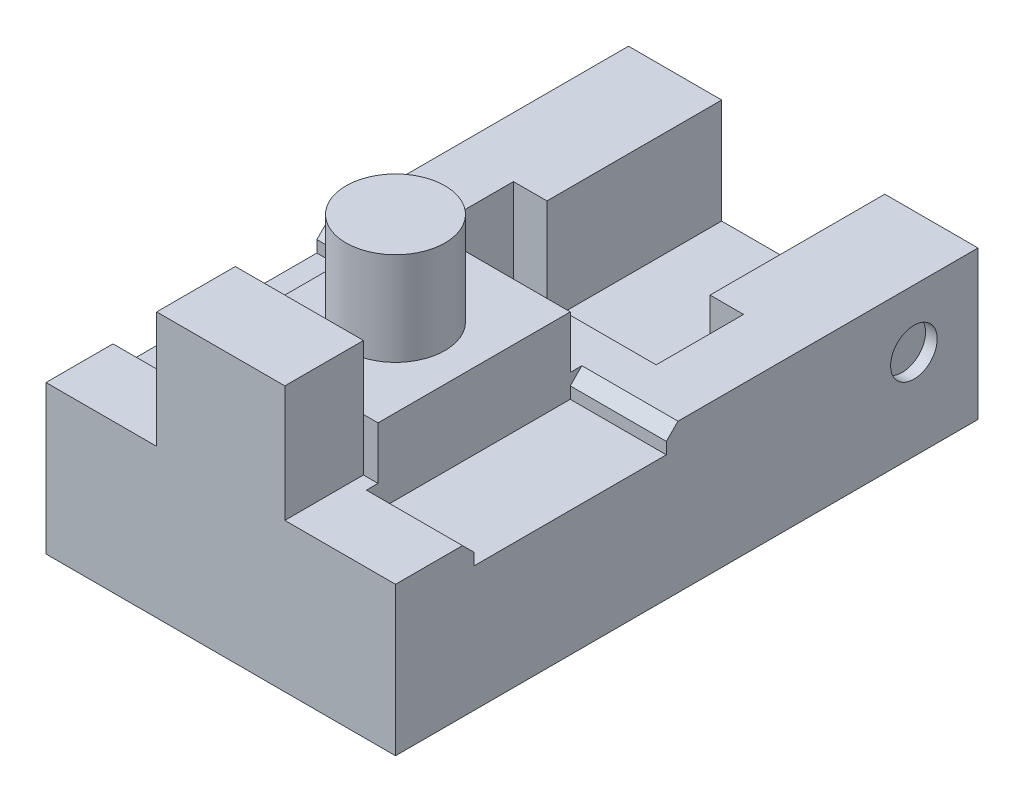
SolidWorks part; units mm, degrees
ref_plane "Front Plane" through (0, 0, 0) normal (0, 0, 1) x (1, 0, 0)
ref_plane "Top Plane" through (0, 0, 0) normal (0, 1, 0) x (1, 0, 0)
ref_plane "Right Plane" through (0, 0, 0) normal (1, 0, 0) x (0, 0, -1)
sketch "Sketch1" plane through (0, 0, 0) normal (0, 1, 0) x (1, 0, 0)
  line L0 (-1.4, 3) -> (-1.4, 0)
  line L1 (-1.4, 0) -> (-1.975, 0)
  line L2 (-1.975, 0) -> (-1.975, -1.5)
  line L4 (-3, -7) -> (-3, 3)
  line L5 (-3, 3) -> (-1.4, 3)
  line L6 (1.4, 0) -> (1.4, 3)
  line L7 (1.4, 3) -> (3, 3)
  line L8 (3, 3) -> (3, -7)
  line L10 (1.975, -1.5) -> (1.975, 0)
  line L11 (1.975, 0) -> (1.4, 0)
  line L12 (-1.4, 0) -> (1.4, 0) construction
  line L13 (-1.975, -1.5) -> (1.975, -1.5)
  line L14 (-3, -7) -> (3, -7)
  circle A0 centre (0, -5) radius 1.8126 construction
  dimension "D1" = 2.8
  dimension "D2" = 3.95
  dimension "D3" = 3
  dimension "D4" = 5
  dimension "D5" = 6
  dimension "D6" = 1.5
  dimension "D7" = 7
extrude "Boss-Extrude1" add sketch "Sketch1" along normal blind 1.8
sketch "Sketch2" plane through (0, 0, 0) normal (0, -1, 0) x (1, 0, 0)
  line L0 (-3, 7) -> (3, 7) construction
  line L1 (-3, 7) -> (3, 7)
  line L2 (-3, -3) -> (-3, 7) construction
  line L3 (-3, -3) -> (-3, 7)
  line L4 (3, 7) -> (3, -3) construction
  line L5 (3, 7) -> (3, -3)
  line L6 (-3, -3) -> (3, -3)
extrude "Boss-Extrude2" add sketch "Sketch2" along normal blind 0.75
sketch "Sketch3" plane through (0, 1.8, 0) normal (0, 1, 0) x (1, 0, 0)
  line L1 (1.35, -5.65) -> (-1.35, -5.65)
  line L2 (1.35, -5.65) -> (1.35, -2.35)
  line L3 (1.35, -2.35) -> (-1.35, -2.35)
  line L4 (-1.35, -5.65) -> (-1.35, -2.35)
  line L5 (1.35, -5.65) -> (-1.35, -2.35) construction
  line L6 (1.35, -2.35) -> (-1.35, -5.65) construction
  line L8 (-1.975, 0) -> (-1.4, 0) construction
  point P0 (0, -4)
  dimension "D1" = 2.7
  dimension "D2" = 3.3
  dimension "D3" = 4
extrude "Boss-Extrude3" add sketch "Sketch3" along normal blind 0.9
sketch "Sketch4" plane through (0, 2.7, 0) normal (0, 1, 0) x (1, 0, 0)
  line L0 (-1.35, -2.35) -> (1.35, -5.65) construction
  circle A0 centre (0, -4) radius 0.85
  dimension "D1" = 1.7
extrude "Boss-Extrude4" add sketch "Sketch4" along normal blind 1.6
sketch "Sketch5" plane through (0, 1.8, 0) normal (0, 1, 0) x (1, 0, 0)
  line L0 (-1.35, -5.65) -> (1.35, -5.65) construction
  line L1 (-1.1, -5.65) -> (1.1, -5.65)
  line L2 (-1.1, -5.65) -> (-1.1, -7)
  line L3 (-1.1, -7) -> (1.1, -7)
  line L4 (1.1, -5.65) -> (1.1, -7)
  line L5 (-3, -7) -> (3, -7) construction
  point P8 (0, -5.65)
  dimension "D1" = 2.2
extrude "Boss-Extrude5" add sketch "Sketch5" along normal blind 2
sketch "Sketch7" plane through (0, 1.8, 0) normal (0, 1, 0) x (1, 0, 0)
  line L0 (-3, 3) -> (-3, -7) construction
  line L1 (-1.35, -2.35) -> (-3, -2.35)
  line L2 (-1.35, -2.35) -> (-1.35, -5.65)
  line L3 (-1.35, -5.65) -> (-3, -5.65)
  line L4 (-3, -2.35) -> (-3, -5.65)
  line L5 (3, -7) -> (3, 3) construction
  line L6 (1.35, -5.65) -> (3, -5.65)
  line L7 (1.35, -5.65) -> (1.35, -2.35)
  line L8 (1.35, -2.35) -> (3, -2.35)
  line L9 (3, -5.65) -> (3, -2.35)
  line L10 (1.35, -2.35) -> (-1.35, -2.35) construction
  point P16 (0, 0)
extrude "Cut-Extrude2" cut sketch "Sketch7" against normal blind 0.4
chamfer "Chamfer1" distance 0.2 angle 45 4 edges at (-2.175, 1.8, 5.65) (-2.175, 1.8, 2.35) (2.175, 1.8, 2.35) (2.175, 1.8, 5.65)
sketch "Sketch9" plane through (3, 0, 0) normal (1, 0, 0) x (0, 0, -1)
  line L0 (-2.15, 1.8) -> (3, 1.8) construction
  line L1 (3, 1.8) -> (3, -0.75) construction
  circle A0 centre (1.9, 0.8) radius 0.4
  point P2 (0, 0)
  dimension "D1" = 0.8
  dimension "D2" = 1
  dimension "D3" = 1.1
extrude "Cut-Extrude4" cut sketch "Sketch9" against normal blind 0.2
mirror "Mirror1" about plane through (0, 0, 0) normal (1, 0, 0) of "Cut-Extrude4"
